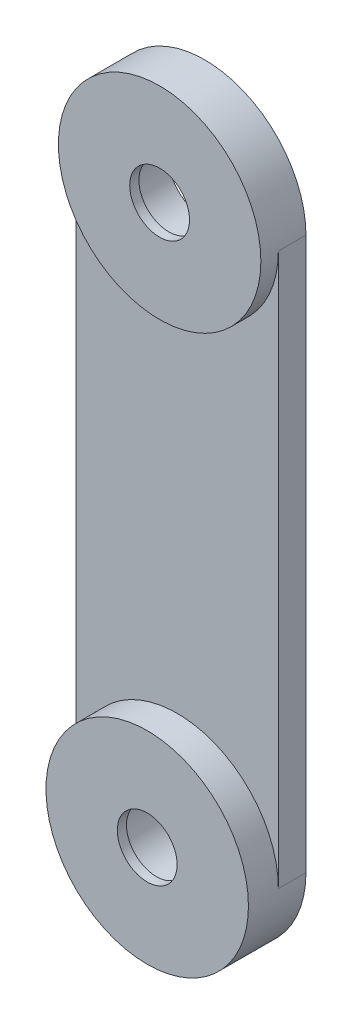
SolidWorks part; units mm, degrees
ref_plane "Plano frontal" through (0, 0, 0) normal (0, 0, 1) x (1, 0, 0)
ref_plane "Plano superior" through (0, 0, 0) normal (0, 1, 0) x (1, 0, 0)
ref_plane "Plano direito" through (0, 0, 0) normal (1, 0, 0) x (0, 0, -1)
sketch "Esboço1" plane through (0, 0, 0) normal (0, 0, 1) x (1, 0, 0)
  circle A3 centre (13.3842, -8.4275) radius 11 construction
  circle A5 centre (13.3842, -8.4275) radius 11
extrude "Ressalto-extrusão1" add sketch "Esboço1" against normal offset from surface (1.9 mm away) 2
sketch "Esboço3" plane through (0, 0, -1.9) normal (0, 0, -1) x (-1, 0, 0)
  line L0 (-24.3842, -8.4275) -> (-24.3842, -68.4275)
  line L1 (-2.3842, -8.4275) -> (-2.3842, -68.4275)
  arc A0 (-24.3842, -68.4275) -> (-2.3842, -68.4275) centre (-13.3842, -68.4275) ccw
  arc A7 (-2.3842, -8.4275) -> (-24.3842, -8.4275) centre (-13.3842, -8.4275) ccw
  circle A8 centre (-13.3842, -8.4275) radius 11 construction
  dimension "D1" = 60
extrude "Ressalto-extrusão3" add sketch "Esboço3" along normal blind 3
sketch "Esboço4" plane through (0, 0, -4.9) normal (0, 0, -1) x (-1, 0, 0)
  circle A0 centre (-13.3842, -8.4275) radius 3.25 construction
  circle A1 centre (-13.3842, -8.4275) radius 3.25
extrude "Corte-extrusão2" cut sketch "Esboço4" against normal through all
sketch "Esboço5" plane through (0, 0, -4.9) normal (0, 0, -1) x (-1, 0, 0)
  circle A0 centre (-13.3842, -8.4275) radius 4 construction
  circle A1 centre (-13.3842, -8.4275) radius 4
extrude "Corte-extrusão5" cut sketch "Esboço5" against normal offset from surface (3.9 mm away) 1 up to face at (10.1342, -8.4275, 0)
sketch "Esboço6" plane through (0, 0, -1.9) normal (0, 0, 1) x (1, 0, 0)
  circle A0 centre (13.3842, -68.4275) radius 11
  arc A1 (2.3842, -68.4275) -> (24.3842, -68.4275) centre (13.3842, -68.4275) ccw construction
extrude "Ressalto-extrusão4" add sketch "Esboço6" along normal offset from surface (3.25 mm away) 1
sketch "Esboço7" plane through (0, 0, -4.9) normal (0, 0, -1) x (-1, 0, 0)
  circle A0 centre (-13.3842, -68.4275) radius 4 construction
  circle A1 centre (-13.3842, -68.4275) radius 4
extrude "Corte-extrusão6" cut sketch "Esboço7" against normal offset from surface (5.25 mm away) 1 up to face at (13.3842, -79.4275, 1.35)
sketch "Esboço8" plane through (0, 0, -4.9) normal (0, 0, -1) x (-1, 0, 0)
  circle A0 centre (-13.3842, -68.4275) radius 3.25 construction
  circle A1 centre (-13.3842, -68.4275) radius 3.25
extrude "Corte-extrusão7" cut sketch "Esboço8" against normal through all
